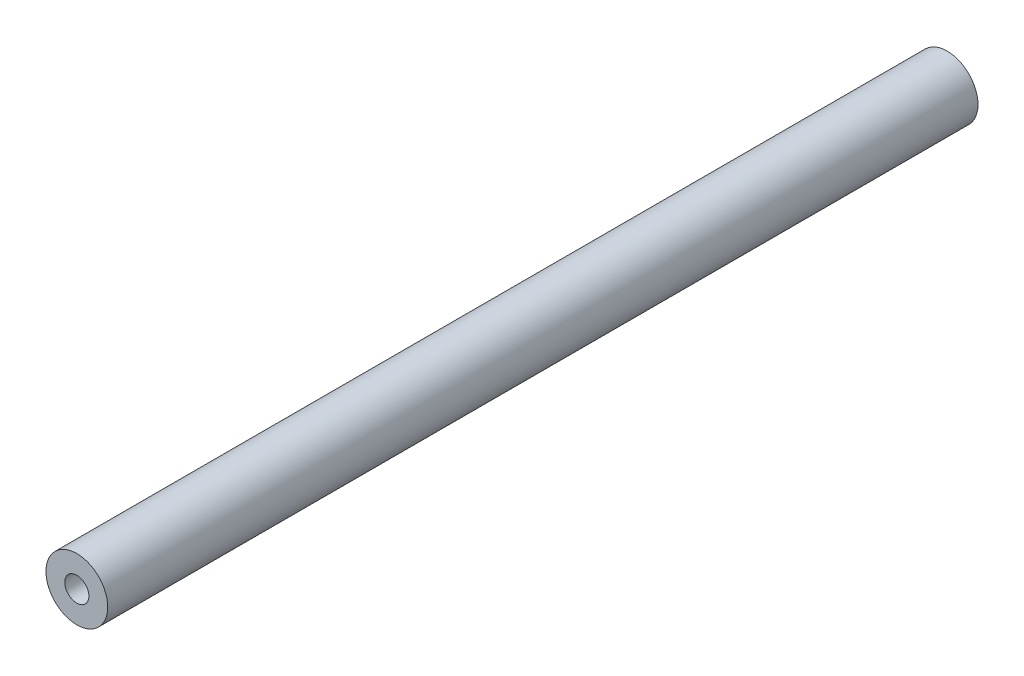
SolidWorks part; units mm, degrees
ref_plane "Front Plane" through (0, 0, 0) normal (0, 0, 1) x (1, 0, 0)
ref_plane "Top Plane" through (0, 0, 0) normal (0, 1, 0) x (1, 0, 0)
ref_plane "Right Plane" through (0, 0, 0) normal (1, 0, 0) x (0, 0, -1)
sketch "Sketch1" plane through (0, 0, 0) normal (0, 0, 1) x (1, 0, 0)
  circle A0 centre (0, 0) radius 5.5
  dimension "D1" = 11
extrude "Boss-Extrude1" add sketch "Sketch1" along normal blind 155
sketch "Sketch2" plane through (0, 0, 155) normal (0, 0, 1) x (1, 0, 0)
  circle A0 centre (0, 0) radius 2.15
  dimension "D1" = 4.3
extrude "Cut-Extrude1" cut sketch "Sketch2" against normal blind 150
